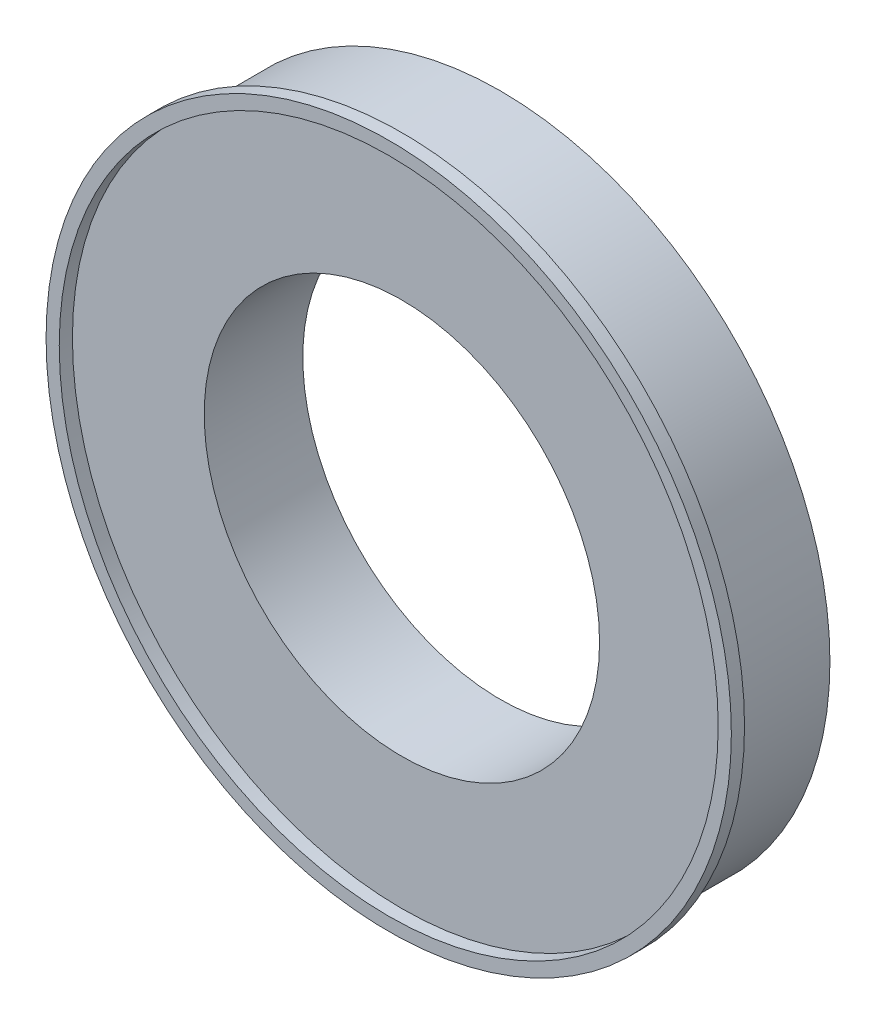
SolidWorks part; units mm, degrees
ref_plane "Front Plane" through (0, 0, 0) normal (0, 0, 1) x (1, 0, 0)
ref_plane "Top Plane" through (0, 0, 0) normal (0, 1, 0) x (1, 0, 0)
ref_plane "Right Plane" through (0, 0, 0) normal (1, 0, 0) x (0, 0, -1)
sketch "Sketch1" plane through (0, 0, 0) normal (0, 0, 1) x (1, 0, 0)
  circle A0 centre (0, 0) radius 63.5
  circle A1 centre (0, 0) radius 38.1
  dimension "D1" = 127
  dimension "D2" = 76.2
extrude "Boss-Extrude1" add sketch "Sketch1" along normal mid plane 19
sketch "Sketch2" plane through (0, 0, 9.5) normal (0, 0, 1) x (1, 0, 0)
  circle A0 centre (0, 0) radius 63.5 construction
  circle A1 centre (0, 0) radius 63.5
  circle A2 centre (0, 0) radius 66.04
  dimension "D1" = 2.54
extrude "Boss-Extrude2" add sketch "Sketch2" along normal blind 2.54 separate body
